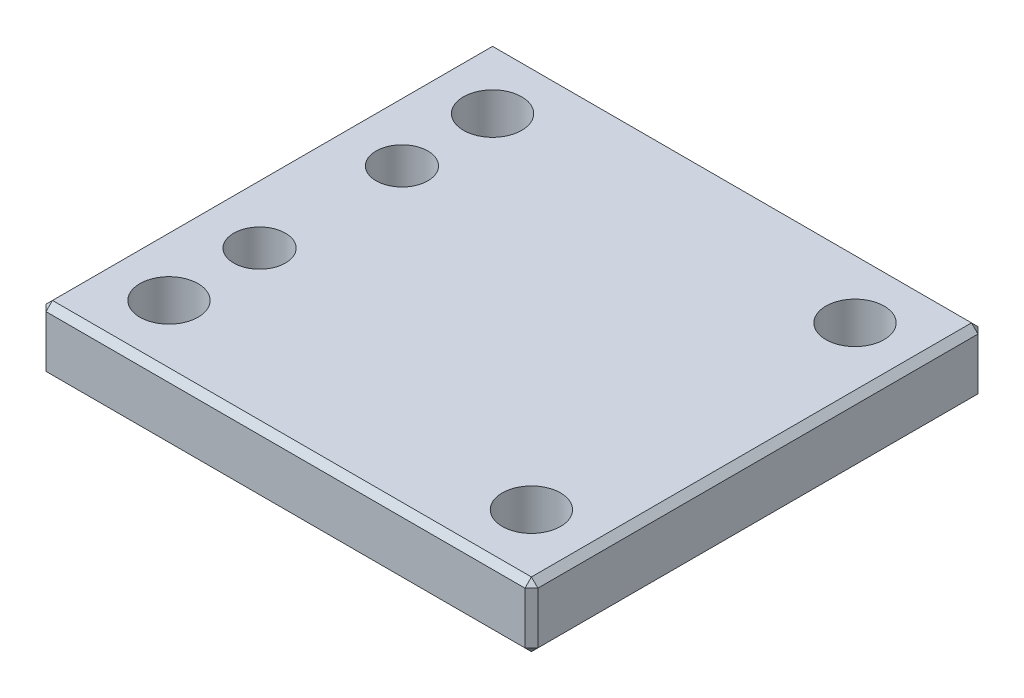
SolidWorks part; units mm, degrees
ref_plane "前视基准面" through (0, 0, 0) normal (0, 0, 1) x (1, 0, 0)
ref_plane "上视基准面" through (0, 0, 0) normal (0, 1, 0) x (1, 0, 0)
ref_plane "右视基准面" through (0, 0, 0) normal (1, 0, 0) x (0, 0, -1)
sketch "草图1" plane through (0, 0, 0) normal (0, 1, 0) x (1, 0, 0)
  line L1 (0, 0) -> (38, 0)
  line L2 (0, 0) -> (0, 35)
  line L3 (0, 35) -> (38, 35)
  line L4 (38, 0) -> (38, 35)
  dimension "D1" = 38
  dimension "D2" = 35
extrude "凸台-拉伸1" add sketch "草图1" along normal blind 5
chamfer "倒角1" distance 0.5 angle 45 12 edges at (38, 2.5, -35) (0, 2.5, -35) (0, 2.5, 0) (19, 0, 0) (0, 0, -17.5) (19, 0, -35) (38, 0, -17.5) (38, 2.5, 0) (19, 5, -35) (38, 5, -17.5) (19, 5, 0) (0, 5, -17.5)
sketch "草图2" plane through (0, 0, 0) normal (0, -1, 0) x (1, 0, 0)
  circle A0 centre (5, -5) radius 2.25
  circle A1 centre (5, -30) radius 2.25
  circle A2 centre (33, -30) radius 2.25
  circle A3 centre (33, -5) radius 2.25
  circle A4 centre (5, -12) radius 2
  circle A5 centre (5, -23) radius 2
  dimension "D1" = 4.5
extrude "切除-拉伸1" cut sketch "草图2" against normal through all
